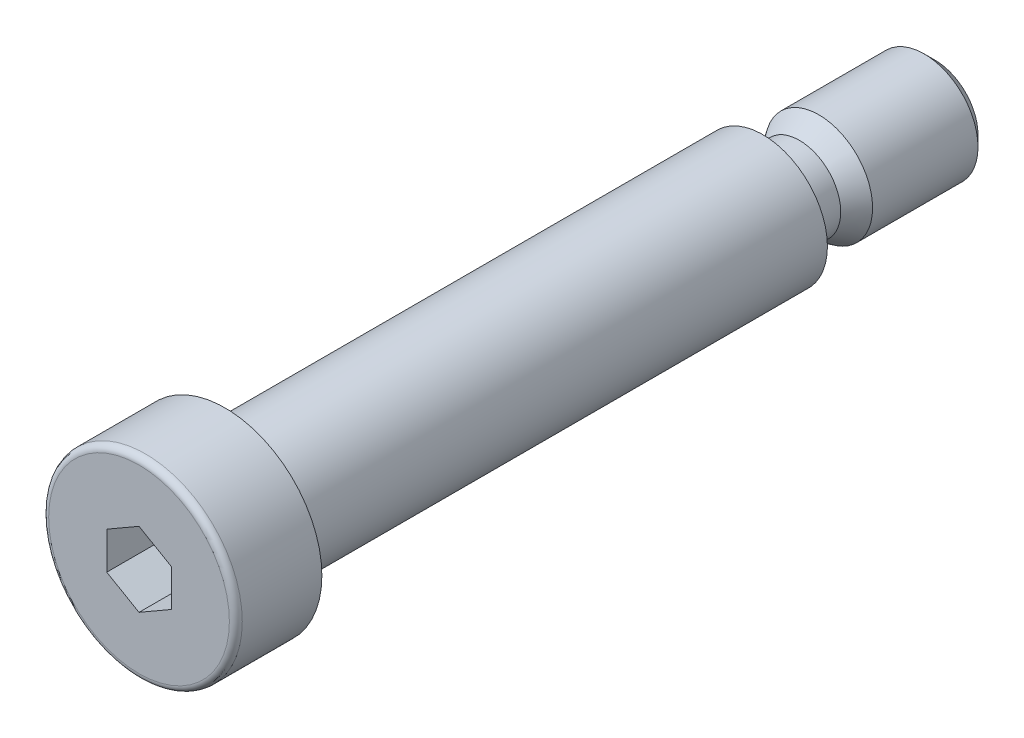
SolidWorks part; units mm, degrees
material "1.0545 (S355N)"
ref_plane "Płaszczyzna przednia" through (0, 0, 0) normal (0, 0, 1) x (1, 0, 0)
ref_plane "Płaszczyzna górna" through (0, 0, 0) normal (0, 1, 0) x (1, 0, 0)
ref_plane "Płaszczyzna prawa" through (0, 0, 0) normal (1, 0, 0) x (0, 0, -1)
sketch "Szkic1" plane through (0, 0, 0) normal (0, 1, 0) x (1, 0, 0)
  line L0 (5, 30.2) -> (3.85, 28.39)
  line L1 (9, -33) -> (-9, -33)
  line L2 (9, -33) -> (9, -25)
  line L3 (9, -25) -> (-9, -25)
  line L4 (-9, -33) -> (-9, -25)
  line L5 (6, -25) -> (-6, -25)
  line L6 (6, -25) -> (6, 25)
  line L7 (6, 25) -> (-6, 25)
  line L8 (-6, -25) -> (-6, 25)
  line L9 (-3.85, 25) -> (3.85, 25)
  line L10 (-3.85, 25) -> (-3.85, 28.39)
  line L11 (-3.85, 28.39) -> (3.85, 28.39)
  line L12 (3.85, 25) -> (3.85, 28.39)
  line L13 (5, 30.2) -> (5, 40)
  line L14 (5, 40) -> (4, 41)
  line L15 (4, 41) -> (-4, 41)
  line L16 (-4, 41) -> (-5, 40)
  line L17 (-5, 40) -> (-5, 30.2)
  line L18 (-5, 30.2) -> (-3.85, 28.39)
  line L19 (5, 30.2) -> (-5, 30.2) construction
  line L20 (5, 40) -> (-5, 40) construction
  line L21 (0, -19.9356) -> (0, 25.6583) construction
  line L22 (0, -33) -> (0, 41)
  point P4 (0, -25)
  point P14 (0, -25)
  point P15 (0, 25)
  point P16 (0, 25)
  point P17 (-6, 0)
  point P23 (0, 30.2)
  point P25 (0, 41)
  point P26 (0, 28.39)
  point P27 (0, 40)
  dimension "D1" = 18
  dimension "D2" = 8
  dimension "D3" = 12
  dimension "l1" = 50
  dimension "D5" = 7.7
  dimension "D6" = 16
  dimension "D7" = 10
  dimension "D8" = 8
  dimension "D9" = 1
  dimension "D10" = 1.81
  dimension "D11" = 9.8
revolve "Obrót1" add sketch "Szkic1" angle 360 about L22
sketch "Szkic2" plane through (0, 0, 33) normal (0, 0, 1) x (1, 0, 0)
  line L1 (3, 1.7321) -> (0, 3.4641)
  line L2 (0, 3.4641) -> (-3, 1.7321)
  line L3 (-3, 1.7321) -> (-3, -1.7321)
  line L4 (-3, -1.7321) -> (0, -3.4641)
  line L5 (0, -3.4641) -> (3, -1.7321)
  line L6 (3, -1.7321) -> (3, 1.7321)
  circle A0 centre (0, 0) radius 3 construction
  dimension "D1" = 6
extrude "Wytnij-wyciągnięcie1" cut sketch "Szkic2" against normal blind 4.9
fillet "Zaokrąglenie1" radius 0.6 1 edges at (9, 0, 33)
